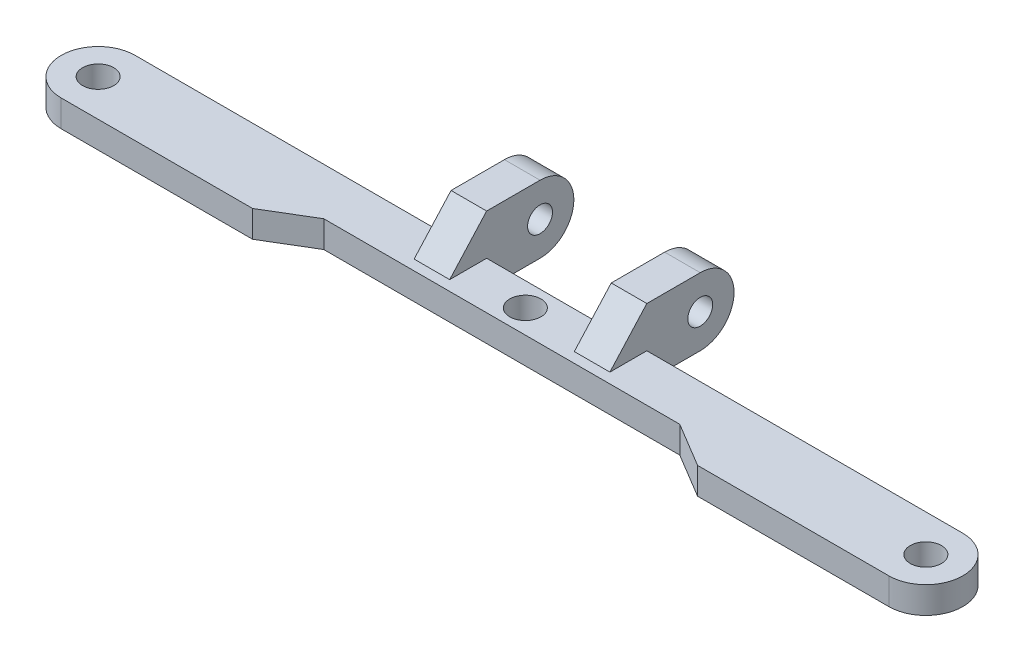
SolidWorks part; units mm, degrees
material "S235JR"
ref_plane "Piano X" through (0, 0, 0) normal (0, 0, 1) x (1, 0, 0)
ref_plane "Piano Y" through (0, 0, 0) normal (0, 1, 0) x (1, 0, 0)
ref_plane "Piano Z" through (0, 0, 0) normal (1, 0, 0) x (0, 0, -1)
sketch "Schizzo1" plane through (0, 0, 0) normal (0, 1, 0) x (1, 0, 0)
  line L1 (-46.5, -4.15) -> (46.5, -4.15)
  line L3 (-46.5, 4.15) -> (46.5, 4.15)
  line L5 (0, 4.15) -> (0, -4.15) construction
  line L6 (-46.5, 0) -> (46.5, 0) construction
  arc A0 (46.5, -4.15) -> (46.5, 4.15) centre (46.5, 0) ccw
  arc A1 (-46.5, 4.15) -> (-46.5, -4.15) centre (-46.5, 0) ccw
  circle A2 centre (46.5, 0) radius 1.75
  circle A3 centre (-46.5, 0) radius 1.75
  point P0 (0, 0)
  dimension "D2" = 3.5
  dimension "D1" = 93
  dimension "D3" = 2.4
  dimension "D4" = 8.3
extrude "Estrusione-Estrusione1" add sketch "Schizzo1" along normal blind 3
sketch "Schizzo2" plane through (0, 0, 0) normal (1, 0, 0) x (0, 0, -1)
  line L0 (10.15, 7.6) -> (4.15, 7.6)
  line L2 (4.15, 0) -> (10.15, 0)
  line L3 (10.15, 3.8) -> (4.15, 3.8) construction
  line L4 (4.15, 7.6) -> (0, 3)
  line L5 (4.15, 3) -> (-4.15, 3) construction
  line L6 (0, 3) -> (4.15, 3)
  line L7 (4.15, 3) -> (4.15, 0)
  circle A0 centre (10.15, 3.8) radius 1.4
  arc A1 (10.15, 0) -> (10.15, 7.6) centre (10.15, 3.8) ccw
  dimension "D1" = 2.8
  dimension "D2" = 2.4
  dimension "D3" = 6
extrude "Estrusione-Estrusione2" add sketch "Schizzo2" against normal blind 4 from offset 11
mirror "Specchia1" about plane through (0, 0, 0) normal (1, 0, 0) of "Estrusione-Estrusione2"
sketch "Schizzo3" plane through (0, 3, 0) normal (0, 1, 0) x (1, 0, 0)
  line L0 (-25, -4.15) -> (-20, -1.15)
  line L1 (-46.5, -4.15) -> (46.5, -4.15) construction
  line L2 (-20, -1.15) -> (20, -1.15)
  line L3 (20, -1.15) -> (25, -4.15)
  line L4 (25, -4.15) -> (-25, -4.15)
  line L5 (0, 0) -> (0, -1.15) construction
  dimension "D1" = 50
  dimension "D2" = 40
  dimension "D3" = 3
extrude "Taglio-Estrusione1" cut sketch "Schizzo3" against normal through all
sketch "Schizzo4" plane through (0, 3, 0) normal (0, 1, 0) x (1, 0, 0)
  line L0 (0, 1.5) -> (0, 0) construction
  line L1 (7, 4.15) -> (-7, 4.15) construction
  circle A0 centre (0, 1.5) radius 1.75
  dimension "D2" = 3.5
  dimension "D1" = 2.65
extrude "Taglio-Estrusione2" cut sketch "Schizzo4" against normal through all
equation "\"D3@Schizzo1\"=0.4*6"
equation "\"D2@Schizzo2\"=0.4*6"
